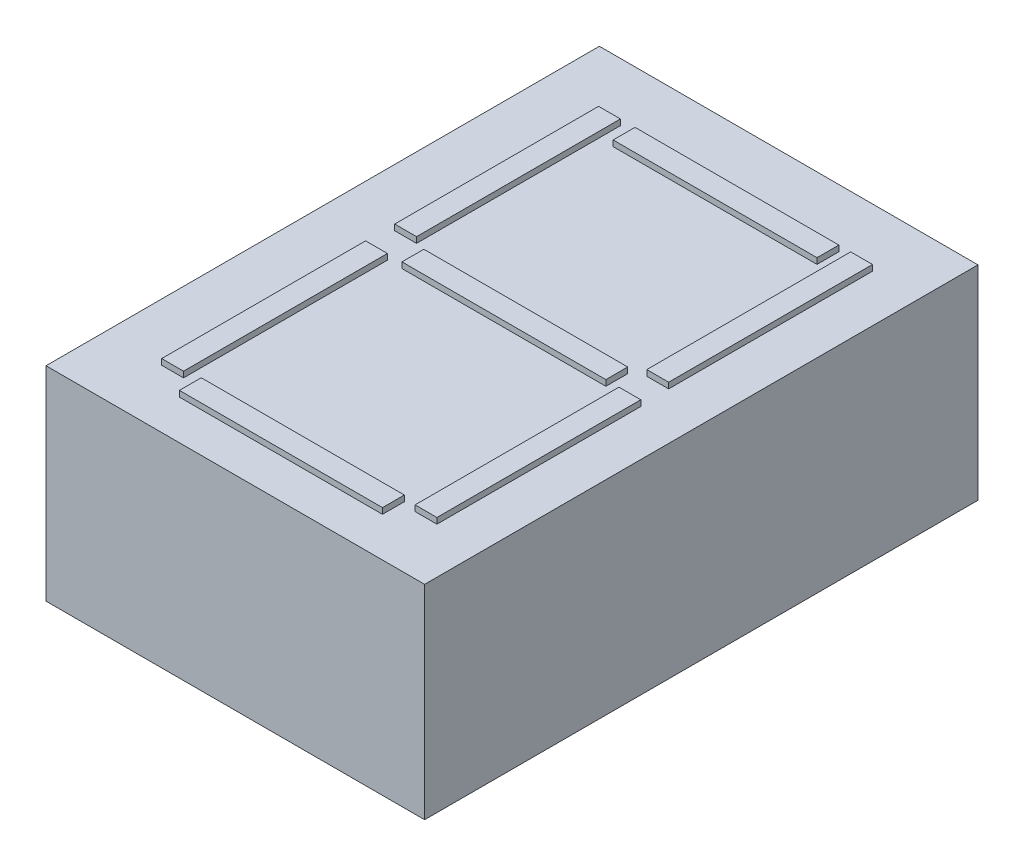
SolidWorks part; units mm, degrees
material "ABS"
ref_plane "Front Plane" through (0, 0, 0) normal (0, 0, 1) x (1, 0, 0)
ref_plane "Top Plane" through (0, 0, 0) normal (0, 1, 0) x (1, 0, 0)
ref_plane "Right Plane" through (0, 0, 0) normal (1, 0, 0) x (0, 0, -1)
sketch "Sketch1" plane through (0, 0, 0) normal (0, 1, 0) x (1, 0, 0)
  line L1 (0, 0.1365) -> (13, 0.1365)
  line L2 (0, 0.1365) -> (0, -18.8635)
  line L3 (0, -18.8635) -> (13, -18.8635)
  line L4 (13, 0.1365) -> (13, -18.8635)
  dimension "D1" = 13
  dimension "D2" = 19
extrude "Boss-Extrude1" add sketch "Sketch1" along normal blind 7
sketch "Sketch2" plane through (0, 7, 0) normal (0, 1, 0) x (1, 0, 0)
  line L0 (13, 0.1365) -> (0, 0.1365) construction
  line L1 (3.2227, -1.8635) -> (10.2227, -1.8635)
  line L2 (3.2227, -1.8635) -> (3.2227, -2.6135)
  line L3 (3.2227, -2.6135) -> (10.2227, -2.6135)
  line L4 (10.2227, -1.8635) -> (10.2227, -2.6135)
  line L5 (1.9727, -1.8635) -> (2.7227, -1.8635)
  line L6 (1.9727, -1.8635) -> (1.9727, -8.8635)
  line L7 (1.9727, -8.8635) -> (2.7227, -8.8635)
  line L8 (2.7227, -1.8635) -> (2.7227, -8.8635)
  line L9 (10.6283, -1.8635) -> (11.3783, -1.8635)
  line L10 (10.6283, -1.8635) -> (10.6283, -8.8635)
  line L11 (10.6283, -8.8635) -> (11.3783, -8.8635)
  line L12 (11.3783, -1.8635) -> (11.3783, -8.8635)
  line L13 (3.2227, -9.1135) -> (10.2227, -9.1135)
  line L14 (3.2227, -9.1135) -> (3.2227, -9.8635)
  line L15 (3.2227, -9.8635) -> (10.2227, -9.8635)
  line L16 (10.2227, -9.1135) -> (10.2227, -9.8635)
  line L17 (2.7227, -9.8635) -> (1.9727, -9.8635)
  line L18 (2.7227, -9.8635) -> (2.7227, -16.8635)
  line L19 (2.7227, -16.8635) -> (1.9727, -16.8635)
  line L20 (1.9727, -9.8635) -> (1.9727, -16.8635)
  line L21 (3.2227, -16.7556) -> (10.195, -16.7556)
  line L22 (3.2227, -16.7556) -> (3.2227, -17.5056)
  line L23 (3.2227, -17.5056) -> (10.195, -17.5056)
  line L24 (10.195, -16.7556) -> (10.195, -17.5056)
  line L25 (10.6727, -9.8635) -> (11.4227, -9.8635)
  line L26 (10.6727, -9.8635) -> (10.6727, -16.8635)
  line L27 (10.6727, -16.8635) -> (11.4227, -16.8635)
  line L28 (11.4227, -9.8635) -> (11.4227, -16.8635)
  point P30 (10.2227, -9.4885)
  point P31 (3.2227, -9.4885)
  point P32 (2.3477, -8.8635)
  dimension "D1" = 7
  dimension "D2" = 2
  dimension "D3" = 7
  dimension "D4" = 2
  dimension "D5" = 7
  dimension "D6" = 2
  dimension "D7" = 0.75
  dimension "D8" = 0.75
  dimension "D9" = 0.5
  dimension "D10" = 0.75
  dimension "D11" = 7
  dimension "D12" = 1
  dimension "D13" = 7
  dimension "D14" = 0.75
  dimension "D15" = 6.5
  dimension "D16" = 0.75
  dimension "D17" = 0.45
  dimension "D18" = 0.5
  dimension "D19" = 0.75
  dimension "D20" = 7
  dimension "D21" = 0.5
  dimension "D22" = 1
  dimension "D23" = 0.75
  dimension "D24" = 6.9723
  dimension "D25" = 0.5
extrude "Boss-Extrude2" add sketch "Sketch2" along normal blind 0.2
